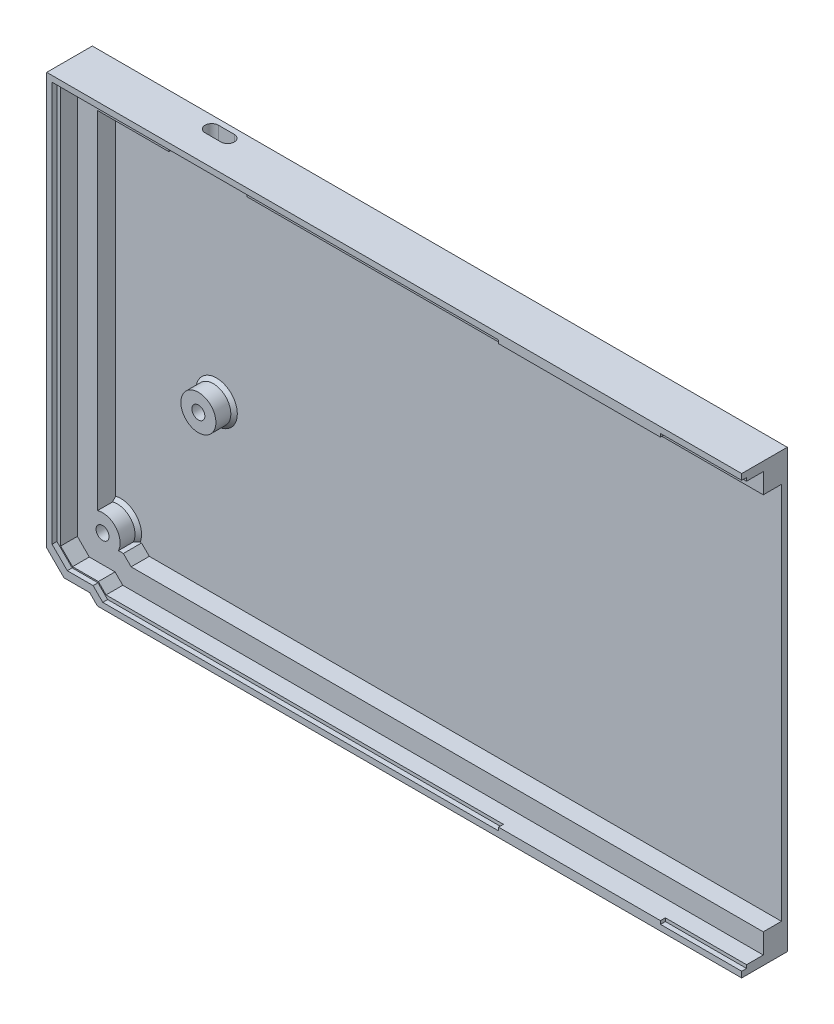
SolidWorks part; units mm, degrees
ref_plane "Přední rovina" through (0, 0, 0) normal (0, 0, 1) x (1, 0, 0)
ref_plane "Horní rovina" through (0, 0, 0) normal (0, 1, 0) x (1, 0, 0)
ref_plane "Pravá rovina" through (0, 0, 0) normal (1, 0, 0) x (0, 0, -1)
sketch "Skica3" plane through (0, 0, 0) normal (0, 0, 1) x (1, 0, 0)
  line L0 (0, 0) -> (415.1053, 0) construction
  line L1 (415.1053, 0) -> (416.6927, -1.5875) construction
  line L2 (416.6927, -1.5875) -> (416.6927, -119.8485) construction
  line L3 (0, 0) -> (-1.5875, -1.5875) construction
  line L4 (-1.5875, -1.5875) -> (-1.5875, -119.8485) construction
  line L5 (-1.5875, -119.8485) -> (0.7934, -122.2292) construction
  line L6 (0.7934, -122.2292) -> (8.7304, -122.2292) construction
  line L7 (8.7304, -122.2292) -> (11.1113, -124.61) construction
  line L8 (11.1113, -124.61) -> (403.9933, -124.61) construction
  line L9 (403.9933, -124.61) -> (406.3744, -122.2294) construction
  line L10 (406.3744, -122.2294) -> (414.3114, -122.2294) construction
  line L11 (416.6927, -119.8485) -> (414.3114, -122.2294) construction
  line L12 (2.4125, -4) -> (412.6927, -4)
  line L13 (412.6927, -4) -> (412.6927, -4)
  line L14 (412.6927, -4) -> (412.6927, -118.1914)
  line L15 (412.6927, -118.1914) -> (412.6547, -118.2294)
  line L16 (404.7177, -118.2294) -> (412.6547, -118.2294)
  line L17 (402.3367, -120.61) -> (404.7177, -118.2294)
  line L18 (12.7681, -120.61) -> (402.3367, -120.61)
  line L19 (10.3872, -118.2292) -> (12.7681, -120.61)
  line L20 (2.4502, -118.2292) -> (10.3872, -118.2292)
  line L21 (2.4125, -118.1915) -> (2.4502, -118.2292)
  line L22 (2.4125, -4) -> (2.4125, -118.1915)
  line L23 (2.4125, -4) -> (2.4125, -4)
  line L24 (-1.5875, -119.8485) -> (415.1053, 0) construction
  line L26 (0, 0) -> (416.6927, -119.8485) construction
  dimension "D1" = 135
  dimension "D2" = 135
  dimension "D3" = 4
  dimension "D4" = 2.245
  dimension "D5" = 2.245
  dimension "D6" = 118.261
  dimension "D7" = 118.261
  dimension "D8" = 3.367
  dimension "D9" = 7.937
  dimension "D10" = 3.367
  dimension "D11" = 392.882
  dimension "D12" = 3.367
  dimension "D13" = 7.937
  dimension "D14" = 3.3674
extrude "Přidat vysunutím1" add sketch "Skica3" along normal blind 5.6
shell "Skořepina1" thickness 1.8
sketch "Skica7" plane through (0, 0, 5.6) normal (0, 0, 1) x (1, 0, 0)
  line L20 (-6.5875, 5) -> (-6.5875, -121.9196)
  line L21 (-6.5875, -121.9196) -> (-1.2775, -127.2292)
  line L22 (-1.2775, -127.2292) -> (6.6595, -127.2292)
  line L23 (6.6595, -127.2292) -> (9.0403, -129.61)
  line L24 (9.0403, -129.61) -> (406.0641, -129.61)
  line L25 (406.0641, -129.61) -> (408.4452, -127.2294)
  line L26 (408.4452, -127.2294) -> (416.3822, -127.2294)
  line L27 (416.3822, -127.2294) -> (421.6927, -121.9198)
  line L28 (421.6927, -121.9198) -> (421.6927, 5)
  line L29 (421.6927, 5) -> (-6.5875, 5)
  line L30 (-6.5875, 5) -> (-6.5875, -121.9196)
  line L31 (-6.5875, -121.9196) -> (-1.2775, -127.2292)
  line L32 (-1.2775, -127.2292) -> (6.6595, -127.2292)
  line L33 (6.6595, -127.2292) -> (9.0403, -129.61)
  line L34 (9.0403, -129.61) -> (406.0641, -129.61)
  line L35 (406.0641, -129.61) -> (408.4452, -127.2294)
  line L36 (408.4452, -127.2294) -> (416.3822, -127.2294)
  line L37 (416.3822, -127.2294) -> (421.6927, -121.9198)
  line L38 (421.6927, -121.9198) -> (421.6927, 5)
  line L39 (421.6927, 5) -> (-6.5875, 5)
  line L40 (-3.7875, 2.2) -> (-3.7875, -120.7598)
  line L41 (-3.7875, -120.7598) -> (-0.1178, -124.4292)
  line L42 (-0.1178, -124.4292) -> (7.8192, -124.4292)
  line L43 (7.8192, -124.4292) -> (10.2001, -126.81)
  line L44 (10.2001, -126.81) -> (404.9045, -126.81)
  line L45 (404.9045, -126.81) -> (407.2855, -124.4294)
  line L46 (407.2855, -124.4294) -> (415.2225, -124.4294)
  line L47 (415.2225, -124.4294) -> (418.8927, -120.7598)
  line L48 (418.8927, -120.7598) -> (418.8927, 2.2)
  line L49 (418.8927, 2.2) -> (-3.7875, 2.2)
  line L50 (-3.7875, 2.2) -> (-3.7875, -120.7598)
  line L51 (-3.7875, -120.7598) -> (-0.1178, -124.4292)
  line L52 (-0.1178, -124.4292) -> (7.8192, -124.4292)
  line L53 (7.8192, -124.4292) -> (10.2001, -126.81)
  line L54 (10.2001, -126.81) -> (404.9045, -126.81)
  line L55 (404.9045, -126.81) -> (407.2855, -124.4294)
  line L56 (407.2855, -124.4294) -> (415.2225, -124.4294)
  line L57 (415.2225, -124.4294) -> (418.8927, -120.7598)
  line L58 (418.8927, -120.7598) -> (418.8927, 2.2)
  line L59 (418.8927, 2.2) -> (-3.7875, 2.2)
  dimension "D2" = 4.4
  dimension "D1" = 7.2
extrude "Přidat vysunutím3" add sketch "Skica7" along normal blind 5.15 separate body
sketch "Skica8" plane through (0, 0, 5.6) normal (0, 0, -1) x (-1, 0, 0)
  line L0 (-421.6927, 5) -> (6.5875, 5)
  line L1 (6.5875, 5) -> (6.5875, -121.9196)
  line L2 (6.5875, 5) -> (6.5875, -121.9196) construction
  line L3 (6.5875, -121.9196) -> (1.2775, -127.2292)
  line L4 (1.2775, -127.2292) -> (-6.6595, -127.2292)
  line L5 (-6.6595, -127.2292) -> (-9.0403, -129.61)
  line L6 (-9.0403, -129.61) -> (-406.0641, -129.61)
  line L7 (-406.0641, -129.61) -> (-408.4452, -127.2294)
  line L8 (-408.4452, -127.2294) -> (-416.3822, -127.2294)
  line L9 (-416.3822, -127.2294) -> (-421.6927, -121.9198)
  line L10 (-421.6927, -121.9198) -> (-421.6927, 5)
  line L11 (-0.6125, -2.2) -> (-0.6125, -118.9371)
  line L12 (-414.4927, -2.2) -> (-0.6125, -2.2) construction
  line L13 (-0.6125, -2.2) -> (-0.6125, -118.9371) construction
  line L14 (-0.6125, -118.9371) -> (-1.7047, -120.0292)
  line L15 (-1.7047, -120.0292) -> (-9.6417, -120.0292)
  line L16 (-9.6417, -120.0292) -> (-12.0226, -122.41)
  line L17 (-12.0226, -122.41) -> (-403.0822, -122.41)
  line L18 (-403.0822, -122.41) -> (-405.4632, -120.0294)
  line L19 (-405.4632, -120.0294) -> (-413.4002, -120.0294) construction
  line L20 (-405.4632, -120.0294) -> (-413.4002, -120.0294)
  line L21 (-413.4002, -120.0294) -> (-414.4927, -118.9371) construction
  line L22 (-413.4002, -120.0294) -> (-414.4927, -118.9371)
  line L23 (-414.4927, -118.9371) -> (-414.4927, -2.2)
  line L24 (-414.4927, -2.2) -> (-0.6125, -2.2)
extrude "Přidat vysunutím4" add sketch "Skica8" along normal up to surface (7.4 mm away) up to face at (207.5525, -96.7211, -1.8)
sketch "Skica11" plane through (0, 0, 10.75) normal (0, 0, 1) x (1, 0, 0)
  line L0 (207.5526, 3.195) -> (207.5526, 5) construction
  line L1 (421.6927, 5) -> (-6.5875, 5) construction
  line L2 (207.5522, -127.805) -> (207.5522, -129.61) construction
  line L3 (9.0403, -129.61) -> (406.0641, -129.61) construction
  line L4 (-4.9474, -58.4598) -> (-6.5875, -58.4598) construction
  line L5 (-6.5875, 5) -> (-6.5875, -121.9196) construction
  line L6 (420.0526, -58.4599) -> (421.6927, -58.4599) construction
  line L7 (421.6927, -121.9198) -> (421.6927, 5) construction
  line L8 (404.9045, -126.81) -> (407.2855, -124.4294) construction
  line L9 (415.2225, -124.4294) -> (418.8927, -120.7598) construction
  line L10 (7.8192, -124.4292) -> (10.2001, -126.81) construction
  line L11 (-3.7875, -120.7598) -> (-0.1178, -124.4292) construction
  line L13 (407.2855, -124.4294) -> (415.2225, -124.4294) construction
  line L14 (-0.1178, -124.4292) -> (7.8192, -124.4292) construction
  line L30 (420.0526, 3.195) -> (-4.9474, 3.195)
  line L31 (-4.9474, 3.195) -> (-4.9474, -120.1146)
  line L32 (-4.9474, -120.1146) -> (-0.24, -124.8217)
  line L33 (-0.24, -124.8217) -> (7.697, -124.8217)
  line L34 (7.697, -124.8217) -> (10.6804, -127.805)
  line L35 (10.6804, -127.805) -> (404.4241, -127.805)
  line L36 (404.4241, -127.805) -> (406.8051, -125.4244)
  line L37 (406.8051, -125.4244) -> (414.7421, -125.4244)
  line L38 (414.7421, -125.4244) -> (420.0526, -120.1148)
  line L39 (420.0526, -120.1148) -> (420.0526, 3.195)
  line L45 (421.6927, 5) -> (-6.5875, 5)
  line L46 (-6.5875, 5) -> (-6.5875, -121.9196)
  line L47 (-6.5875, -121.9196) -> (-1.2775, -127.2292)
  line L48 (-1.2775, -127.2292) -> (6.6595, -127.2292)
  line L49 (6.6595, -127.2292) -> (9.0403, -129.61)
  line L50 (9.0403, -129.61) -> (406.0641, -129.61)
  line L51 (406.0641, -129.61) -> (408.4452, -127.2294)
  line L52 (408.4452, -127.2294) -> (416.3822, -127.2294)
  line L53 (416.3822, -127.2294) -> (421.6927, -121.9198)
  line L54 (421.6927, -121.9198) -> (421.6927, 5)
  line L55 (421.6927, 5) -> (-6.5875, 5)
  line L56 (-6.5875, 5) -> (-6.5875, -121.9196)
  line L57 (-6.5875, -121.9196) -> (-1.2775, -127.2292)
  line L58 (-1.2775, -127.2292) -> (6.6595, -127.2292)
  line L59 (6.6595, -127.2292) -> (9.0403, -129.61)
  line L60 (9.0403, -129.61) -> (406.0641, -129.61)
  line L61 (406.0641, -129.61) -> (408.4452, -127.2294)
  line L62 (408.4452, -127.2294) -> (416.3822, -127.2294)
  line L63 (416.3822, -127.2294) -> (421.6927, -121.9198)
  line L64 (421.6927, -121.9198) -> (421.6927, 5)
  point P0 (207.5523, -63.11)
  point P2 (207.5523, -63.11)
  dimension "D1" = 131
  dimension "D2" = 425
  dimension "D3" = 0
extrude "Přidat vysunutím5" add sketch "Skica11" along normal blind 1.5
sketch "Skica14" plane through (0, 0, 10.75) normal (0, 0, 1) x (1, 0, 0)
  line L0 (418.8927, 2.2) -> (-3.7875, 2.2) construction
  line L1 (182.5326, 2.2) -> (132.6326, 2.2)
  line L2 (182.5326, 2.2) -> (182.5326, 3.195)
  line L3 (182.5326, 3.195) -> (132.6326, 3.195)
  line L4 (132.6326, 2.2) -> (132.6326, 3.195)
  line L5 (420.0526, 3.195) -> (-4.9474, 3.195) construction
  line L6 (418.8927, 2.2) -> (-3.7875, 2.2) construction
  line L7 (232.5726, 2.2) -> (282.4726, 2.2)
  line L8 (232.5726, 2.2) -> (232.5726, 3.195)
  line L9 (232.5726, 3.195) -> (282.4726, 3.195)
  line L10 (282.4726, 2.2) -> (282.4726, 3.195)
  line L11 (207.5526, 3.195) -> (207.5522, -127.805) construction
  line L12 (10.6804, -127.805) -> (404.4241, -127.805) construction
  line L13 (10.2001, -126.81) -> (404.9045, -126.81) construction
  line L14 (232.5722, -126.81) -> (282.4722, -126.81)
  line L15 (232.5722, -126.81) -> (232.5722, -127.805)
  line L16 (232.5722, -127.805) -> (282.4722, -127.805)
  line L17 (282.4722, -126.81) -> (282.4722, -127.805)
  line L18 (10.6804, -127.805) -> (404.4241, -127.805) construction
  line L20 (182.5322, -126.81) -> (132.6322, -126.81)
  line L21 (182.5322, -126.81) -> (182.5322, -127.805)
  line L22 (182.5322, -127.805) -> (132.6322, -127.805)
  line L23 (132.6322, -126.81) -> (132.6322, -127.805)
  dimension "D1" = 49.9
  dimension "D2" = 49.9
  dimension "D3" = 25.02
  dimension "D4" = 25.02
  dimension "D5" = 49.9
  dimension "D6" = 49.9
  dimension "D7" = 25.02
  dimension "D8" = 25.02
extrude "Přidat vysunutím6" add sketch "Skica14" along normal up to surface (1.5 mm away) up to face at (207.5524, -100.1977, 12.25)
sketch "Skica15" plane through (0, 0, 0) normal (0, 0, 1) x (1, 0, 0)
  line L1 (34.9015, 4.5) -> (37.9015, 4.5)
  line L2 (34.9015, 4.5) -> (34.9015, -4.5)
  line L3 (34.9015, -4.5) -> (37.9015, -4.5)
  line L4 (37.9015, 4.5) -> (37.9015, -4.5)
  line L5 (34.9015, 4.5) -> (37.9015, -4.5) construction
  line L6 (34.9015, -4.5) -> (37.9015, 4.5) construction
  line L20 (-1.5875, 0) -> (-1.5875, -119.8485)
  line L21 (-1.5875, -119.8485) -> (0.7934, -122.2292)
  line L22 (0.7934, -122.2292) -> (8.7304, -122.2292)
  line L23 (8.7304, -122.2292) -> (11.1113, -124.61)
  line L24 (11.1113, -124.61) -> (403.9933, -124.61)
  line L25 (403.9933, -124.61) -> (406.3744, -122.2294)
  line L26 (406.3744, -122.2294) -> (414.3114, -122.2294)
  line L27 (414.3114, -122.2294) -> (416.6927, -119.8485)
  line L28 (416.6927, -119.8485) -> (416.6927, 0)
  line L29 (416.6927, 0) -> (-1.5875, 0)
  line L30 (-1.5875, 0) -> (-1.5875, -119.8485) construction
  line L31 (-1.5875, -119.8485) -> (0.7934, -122.2292) construction
  line L32 (0.7934, -122.2292) -> (8.7304, -122.2292) construction
  line L33 (8.7304, -122.2292) -> (11.1113, -124.61) construction
  line L34 (11.1113, -124.61) -> (403.9933, -124.61) construction
  line L35 (403.9933, -124.61) -> (406.3744, -122.2294) construction
  line L36 (406.3744, -122.2294) -> (414.3114, -122.2294) construction
  line L37 (414.3114, -122.2294) -> (416.6927, -119.8485) construction
  line L38 (416.6927, -119.8485) -> (416.6927, 0) construction
  line L39 (416.6927, 0) -> (-1.5875, 0) construction
  circle A0 centre (3.9685, -115.9542) radius 5.4
  circle A1 centre (33.4915, -69.051) radius 5.4
  circle A2 centre (411.1977, -115.8794) radius 5.4
  circle A3 centre (334.1477, -53.972) radius 5.4
  point P2 (-1.4315, -115.9542)
  point P3 (3.9685, -121.3542)
  point P4 (28.0915, -69.051)
  point P8 (33.4915, -74.451)
  point P12 (411.1977, -121.2794)
  point P13 (416.5977, -115.8794)
  point P17 (334.1477, -48.572)
  point P19 (339.5477, -53.972)
  point P21 (36.4015, 0)
  point P23 (36.4015, 0)
  dimension "D2" = 0.156
  dimension "D4" = 10.8
  dimension "D7" = 10.8
  dimension "D10" = 10.8
  dimension "D13" = 10.8
  dimension "D3" = 0.875
  dimension "D5" = 29.679
  dimension "D6" = 50.159
  dimension "D8" = 0.095
  dimension "D9" = 0.95
  dimension "D11" = 77.145
  dimension "D12" = 48.572
  dimension "D14" = 37.989
  dimension "D15" = 9
  dimension "D16" = 3
  dimension "D1" = 4
extrude "Přidat vysunutím7" add sketch "Skica15" along normal blind 5.6
sketch "Skica16" plane through (0, 0, 5.6) normal (0, 0, 1) x (1, 0, 0)
  circle A0 centre (3.9685, -115.9542) radius 2
  circle A1 centre (33.4915, -69.051) radius 2
  circle A2 centre (334.1477, -53.972) radius 2
  circle A3 centre (411.1977, -115.8794) radius 2
  dimension "D1" = 4
  dimension "D2" = 4
  dimension "D3" = 4
  dimension "D4" = 4
extrude "Odebrat vysunutím1" cut sketch "Skica16" against normal blind 5.75
chamfer "Zkosení1" distance 1 angle 45 4 edges at (407.0694, -112.3984, 0) (8.0492, -112.4175, 0) (38.8915, -69.051, 0) (339.5477, -53.972, 0)
sketch "Skica17" plane through (0, 0, 5.6) normal (0, 0, 1) x (1, 0, 0)
  line L0 (34.9015, -4.5) -> (37.9015, -4.5) construction
  line L1 (24.4015, -11.2) -> (48.4015, -11.2)
  line L2 (24.4015, -11.2) -> (24.4015, 2.2)
  line L3 (24.4015, 2.2) -> (48.4015, 2.2)
  line L4 (48.4015, -11.2) -> (48.4015, 2.2)
  line L5 (24.4015, -11.2) -> (48.4015, 2.2) construction
  line L6 (24.4015, 2.2) -> (48.4015, -11.2) construction
  line L7 (418.8927, 2.2) -> (-3.7875, 2.2) construction
  point P0 (36.4015, -4.5)
  dimension "D1" = 24
extrude "Odebrat vysunutím2" cut sketch "Skica17" against normal blind 1.6
sketch "Skica18" plane through (0, -4.5, 0) normal (0, -1, 0) x (1, 0, 0)
  line L0 (33.9515, 1.95) -> (38.8515, 1.95) construction
  line L1 (36.4015, 4) -> (36.4015, 1.95) construction
  line L2 (37.9015, 4) -> (34.9015, 4) construction
  line L3 (33.9515, 4) -> (38.8515, 4)
  line L4 (33.9515, -0.1) -> (38.8515, -0.1)
  arc A0 (33.9515, 4) -> (33.9515, -0.1) centre (33.9515, 1.95) ccw
  arc A1 (38.8515, -0.1) -> (38.8515, 4) centre (38.8515, 1.95) ccw
  point P6 (36.4015, 1.95)
  point P11 (31.9015, 1.95)
  point P12 (40.9015, 1.95)
  dimension "D1" = 9
  dimension "D3" = 2.05
  dimension "D2" = 4.1
extrude "Odebrat vysunutím3" cut sketch "Skica18" against normal up to surface (9.5 mm away) up to face at (207.5526, 5, 5.225)
sketch "Skica23" plane through (-6.5875, 0, 0) normal (-1, 0, 0) x (0, 0, 1)
  line L2 (-1.8, 5) -> (-1.8, -121.9196) construction
  line L4 (-1.8, -58.4598) -> (12.25, -58.4598) construction
  line L5 (12.25, 5) -> (12.25, -121.9196) construction
  circle A0 centre (3.2, -18.4598) radius 2
  circle A1 centre (3.2, -98.4598) radius 2
  point P8 (-1.8, -58.4598)
  dimension "D2" = 4
  dimension "D3" = 4
  dimension "D1" = 40
  dimension "D4" = 5
extrude "Odebrat vysunutím4" cut sketch "Skica23" against normal blind 5.7
sketch "Skica24" plane through (421.6927, 0, 0) normal (1, 0, 0) x (0, 0, -1)
  line L0 (1.8, -58.4599) -> (-12.25, -58.4599) construction
  line L1 (1.8, -121.9198) -> (1.8, 5) construction
  line L2 (-12.25, -121.9198) -> (-12.25, 5) construction
  circle A0 centre (-3.2, -18.4599) radius 2
  circle A1 centre (-3.2, -98.4599) radius 2
  dimension "D1" = 4
  dimension "D2" = 4
  dimension "D3" = 40
  dimension "D4" = 5
extrude "Odebrat vysunutím5" cut sketch "Skica24" against normal blind 5.7
sketch "Skica25" plane through (0, 0, -1.8) normal (0, 0, -1) x (-1, 0, 0)
  line L0 (-421.6927, -121.9198) -> (-421.6927, 5) construction
  line L1 (-421.6927, 5) -> (6.5875, 5) construction
  line L2 (6.5875, 5) -> (6.5875, -121.9196) construction
  line L3 (-9.0403, -129.61) -> (-406.0641, -129.61) construction
  circle A0 centre (-401.6927, -15) radius 6.25
  circle A1 centre (-13.4125, -15) radius 6.25
  circle A2 centre (-388.4452, -109.61) radius 6.25
  circle A3 centre (-26.6595, -109.61) radius 6.25
  dimension "D1" = 12.5
  dimension "D2" = 12.5
  dimension "D3" = 12.5
  dimension "D4" = 12.5
  dimension "D5" = 20
  dimension "D6" = 20
  dimension "D7" = 20
  dimension "D8" = 20
  dimension "D9" = 20
  dimension "D10" = 20
  dimension "D11" = 20
  dimension "D12" = 20
extrude "Odebrat vysunutím6" cut sketch "Skica25" against normal blind 1.5
sketch "Skica26" plane through (0, 5, 0) normal (0, 1, 0) x (1, 0, 0)
  line L0 (207.5526, 1.8) -> (207.5526, -12.25)
  line L1 (421.6927, 1.8) -> (-6.5875, 1.8) construction
  line L2 (421.6927, -12.25) -> (-6.5875, -12.25) construction
  line L3 (207.5526, -12.25) -> (421.6927, -12.25)
  line L4 (421.6927, -12.25) -> (421.6927, 1.8)
  line L5 (421.6927, 1.8) -> (207.5526, 1.8)
extrude "Odebrat vysunutím7" cut sketch "Skica26" against normal through all
